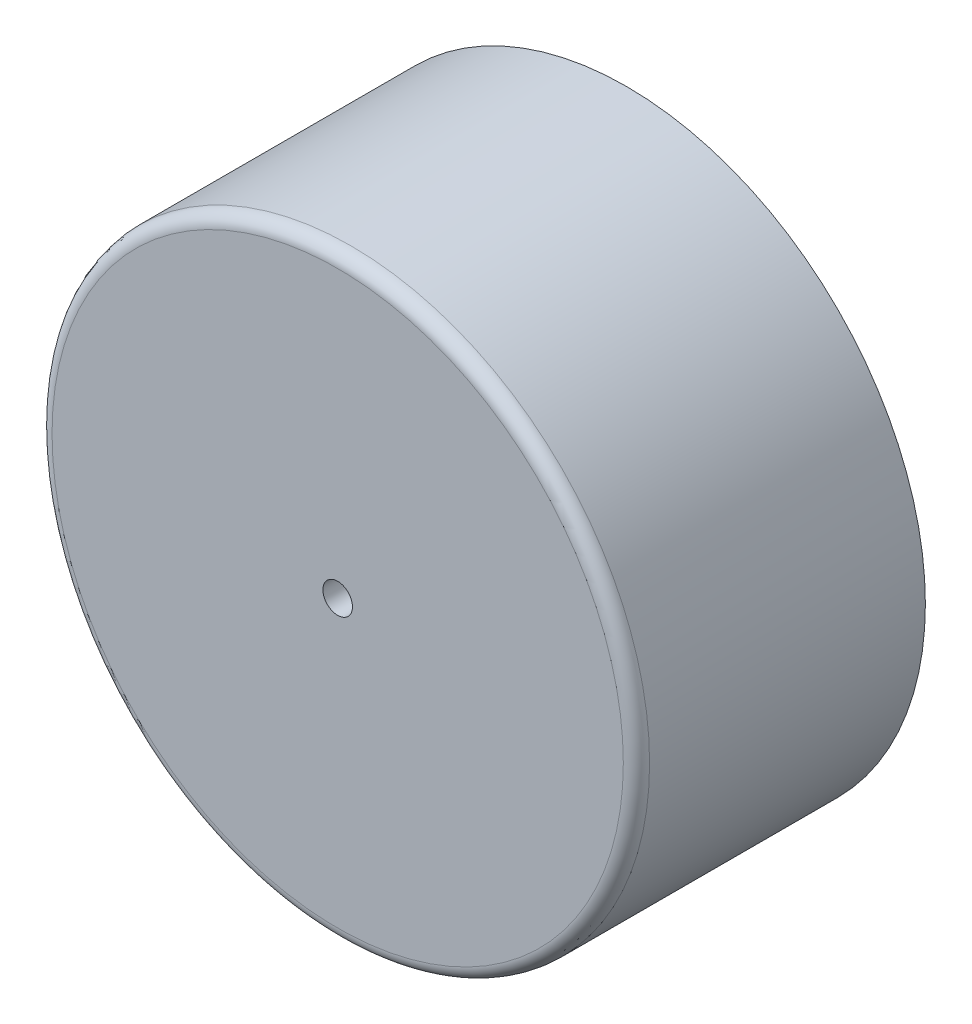
SolidWorks part; units mm, degrees
ref_plane "Front Plane" through (0, 0, 0) normal (0, 0, 1) x (1, 0, 0)
ref_plane "Top Plane" through (0, 0, 0) normal (0, 1, 0) x (1, 0, 0)
ref_plane "Right Plane" through (0, 0, 0) normal (1, 0, 0) x (0, 0, -1)
sketch "Sketch1" plane through (0, 0, 0) normal (0, 0, 1) x (1, 0, 0)
  circle A0 centre (0, 0) radius 22.75
  dimension "D1" = 45.5
extrude "Boss-Extrude1" add sketch "Sketch1" along normal blind 2
sketch "Sketch2" plane through (0, 0, 0) normal (0, 0, -1) x (-1, 0, 0)
  circle A0 centre (0, 0) radius 22.75
  circle A1 centre (0, 0) radius 20.75
  dimension "D1" = 45.5
  dimension "D2" = 2
extrude "Boss-Extrude2" add sketch "Sketch2" along normal blind 20
fillet "Fillet1" radius 1 1 edges at (22.75, 0, 2)
sketch "Sketch3" plane through (0, 0, 2) normal (0, 0, 1) x (1, 0, 0)
  circle A0 centre (0, 0) radius 1.125
  dimension "D1" = 2.25
extrude "Cut-Extrude1" cut sketch "Sketch3" against normal blind 20
